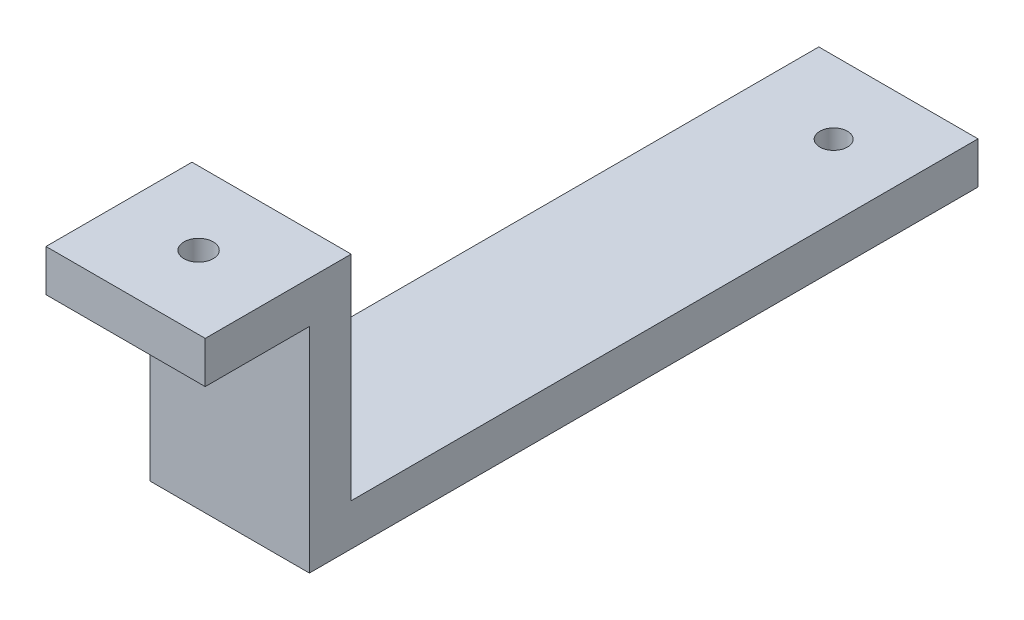
SolidWorks part; units mm, degrees
material "Galvanized Steel"
ref_plane "Front Plane" through (0, 0, 0) normal (0, 0, 1) x (1, 0, 0)
ref_plane "Top Plane" through (0, 0, 0) normal (0, 1, 0) x (1, 0, 0)
ref_plane "Right Plane" through (0, 0, 0) normal (1, 0, 0) x (0, 0, -1)
sketch "Sketch1" plane through (0, 0, 0) normal (1, 0, 0) x (0, 0, -1)
  line L0 (0, 0) -> (34.93, 0)
  line L1 (34.93, 0) -> (34.93, -51.11)
  line L2 (34.93, -51.11) -> (184.93, -51.11)
  dimension "D1" = 34.93
  dimension "D2" = 51.11
extrude "Extrude-Thin1" add sketch "Sketch1" along normal blind 38.1 thin
sketch "Sketch2" plane through (0, 0, 0) normal (0, 1, 0) x (1, 0, 0)
  line L1 (0, 0) -> (0, 34.93) construction
  circle A0 centre (19.05, 17.465) radius 3.5
  dimension "D1" = 19.05
  dimension "D3" = 7
  dimension "D2" = 17.465
extrude "Cut-Extrude1" cut sketch "Sketch2" against normal through all
sketch "Sketch3" plane through (0, -51.11, 0) normal (0, 1, 0) x (1, 0, 0)
  circle A0 centre (19.05, 174.645) radius 3.5
  dimension "D1" = 7
  dimension "D2" = 157.18
sketch "Sketch4" plane through (0, -51.11, 0) normal (0, 1, 0) x (1, 0, 0)
  circle A0 centre (20.8976, 167.5935) radius 3.3
  dimension "D1" = 6.6
extrude "Cut-Extrude3" cut sketch "Sketch4" against normal blind 60
